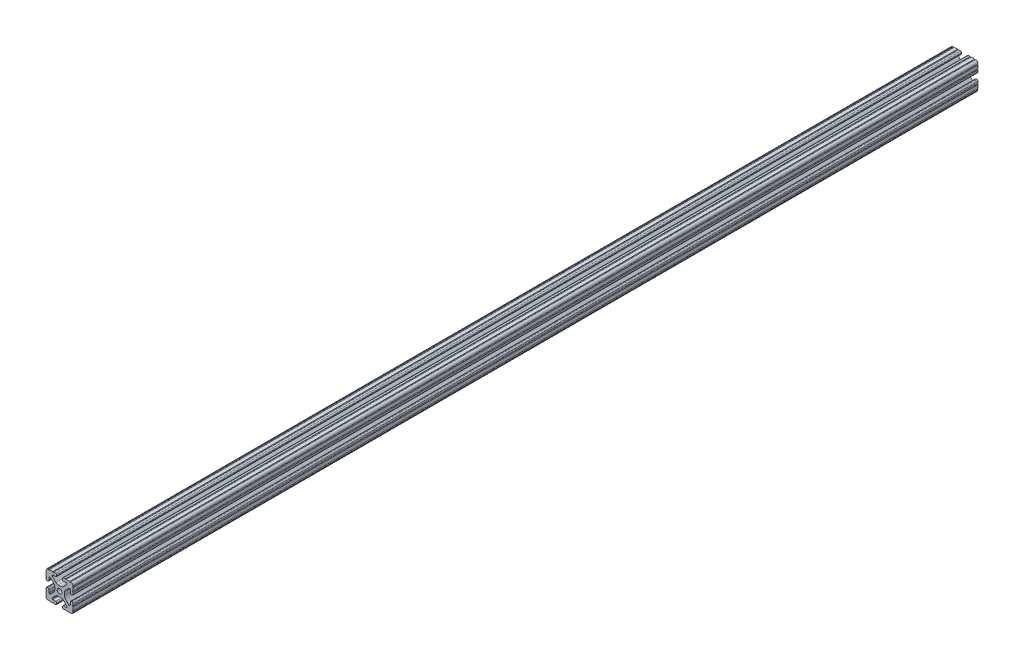
SolidWorks part; units mm, degrees
material "6061 Alloy"
ref_plane "Front Plane" through (0, 0, 0) normal (0, 0, 1) x (1, 0, 0)
ref_plane "Top Plane" through (0, 0, 0) normal (0, 1, 0) x (1, 0, 0)
ref_plane "Right Plane" through (0, 0, 0) normal (1, 0, 0) x (0, 0, -1)
sketch "Sketch1" plane through (0, 0, 0) normal (0, 0, 1) x (1, 0, 0)
  line L0 (0, 25.6181) -> (0, -24.623) construction
  line L1 (-20.8943, 0) -> (20.4607, 0) construction
  line L2 (-10.0229, 12.9148) -> (-5.2522, 8.144)
  line L3 (-10.287, 14.0843) -> (-10.287, 13.5524)
  line L4 (-5.6176, 14.986) -> (-9.3853, 14.986)
  line L5 (-4.064, 17.4964) -> (-4.064, 16.5396)
  line L6 (-7.9742, 19.05) -> (-5.6176, 19.05)
  line L7 (-14.3277, 19.05) -> (-9.4982, 19.05)
  line L8 (-19.05, 9.4961) -> (-19.05, 14.3277)
  line L9 (-19.05, 5.6176) -> (-19.05, 7.9763)
  line L10 (-16.5396, 4.064) -> (-17.4964, 4.064)
  line L11 (-14.986, 9.3853) -> (-14.986, 5.6176)
  line L12 (-13.516, 10.287) -> (-14.0843, 10.287)
  line L13 (-8.1476, 5.2921) -> (-12.8784, 10.0229)
  line L14 (-6.7564, -1.9335) -> (-6.7564, 1.9335)
  line L15 (-12.8784, -10.0229) -> (-8.1476, -5.2921)
  line L16 (-14.0843, -10.287) -> (-13.516, -10.287)
  line L17 (-14.986, -5.6176) -> (-14.986, -9.3853)
  line L18 (-17.4964, -4.064) -> (-16.5396, -4.064)
  line L19 (-19.05, -7.9763) -> (-19.05, -5.6176)
  line L20 (-19.05, -14.3277) -> (-19.05, -9.4961)
  line L21 (-9.4961, -19.05) -> (-14.3277, -19.05)
  line L22 (-5.6176, -19.05) -> (-7.9763, -19.05)
  line L23 (-4.064, -17.4964) -> (-4.064, -16.5396)
  line L24 (10.0229, -12.9148) -> (5.2522, -8.144)
  line L25 (10.287, -14.0843) -> (10.287, -13.5524)
  line L26 (5.6176, -14.986) -> (9.3853, -14.986)
  line L28 (-1.9022, 6.7564) -> (1.9022, 6.7564)
  line L29 (-1.9022, -6.7564) -> (1.9022, -6.7564)
  line L31 (-5.6176, -14.986) -> (-9.3853, -14.986)
  line L32 (-10.287, -14.0843) -> (-10.287, -13.5524)
  line L33 (-10.0229, -12.9148) -> (-5.2522, -8.144)
  line L66 (4.064, -16.5396) -> (4.064, -17.4964)
  line L67 (5.6176, -19.05) -> (7.9763, -19.05)
  line L68 (9.4961, -19.05) -> (14.3277, -19.05)
  line L69 (19.05, -14.3277) -> (19.05, -9.4961)
  line L70 (19.05, -7.9763) -> (19.05, -5.6176)
  line L71 (17.4964, -4.064) -> (16.5396, -4.064)
  line L72 (14.986, -5.6176) -> (14.986, -9.3853)
  line L73 (14.0843, -10.287) -> (13.516, -10.287)
  line L74 (12.8784, -10.0229) -> (8.1476, -5.2921)
  line L75 (6.7564, -1.9335) -> (6.7564, 1.9335)
  line L76 (8.1476, 5.2921) -> (12.8784, 10.0229)
  line L77 (13.516, 10.287) -> (14.0843, 10.287)
  line L78 (14.986, 9.3853) -> (14.986, 5.6176)
  line L79 (16.5396, 4.064) -> (17.4964, 4.064)
  line L80 (19.05, 5.6176) -> (19.05, 7.9763)
  line L81 (19.05, 9.4961) -> (19.05, 14.3277)
  line L82 (14.3277, 19.05) -> (9.4982, 19.05)
  line L83 (7.9742, 19.05) -> (5.6176, 19.05)
  line L84 (4.064, 17.4964) -> (4.064, 16.5396)
  line L85 (5.6176, 14.986) -> (9.3853, 14.986)
  line L86 (10.287, 14.0843) -> (10.287, 13.5524)
  line L87 (10.0229, 12.9148) -> (5.2522, 8.144)
  arc A0 (-10.0229, 12.9148) -> (-10.287, 13.5524) centre (-9.3853, 13.5524) cw
  circle A1 centre (0, 0) radius 3.3274
  arc A2 (-10.287, 14.0843) -> (-9.3853, 14.986) centre (-9.3853, 14.0843) cw
  arc A3 (-4.064, 16.5396) -> (-5.6176, 14.986) centre (-5.6176, 16.5396) cw
  arc A4 (-5.6176, 19.05) -> (-4.064, 17.4964) centre (-5.6176, 17.4964) cw
  arc A5 (-7.9742, 19.05) -> (-9.4982, 19.05) centre (-8.7362, 19.05) cw
  arc A6 (-14.3277, 19.05) -> (-15.8475, 19.05) centre (-15.0876, 18.9933) cw
  arc A7 (-19.05, 15.8475) -> (-15.8475, 19.05) centre (-15.8751, 15.8751) cw
  arc A8 (-19.05, 15.8475) -> (-19.05, 14.3277) centre (-18.9933, 15.0876) cw
  arc A9 (-19.05, 9.4961) -> (-19.05, 7.9763) centre (-18.9933, 8.7362) cw
  arc A10 (-17.4964, 4.064) -> (-19.05, 5.6176) centre (-17.4964, 5.6176) cw
  arc A11 (-14.986, 5.6176) -> (-16.5396, 4.064) centre (-16.5396, 5.6176) cw
  arc A12 (-14.986, 9.3853) -> (-14.0843, 10.287) centre (-14.0843, 9.3853) cw
  arc A13 (-13.516, 10.287) -> (-12.8784, 10.0229) centre (-13.516, 9.3853) cw
  arc A14 (-8.1476, 5.2921) -> (-6.7564, 1.9335) centre (-11.5062, 1.9335) cw
  arc A15 (-6.7564, -1.9335) -> (-8.1476, -5.2921) centre (-11.5062, -1.9335) cw
  arc A16 (-12.8784, -10.0229) -> (-13.516, -10.287) centre (-13.516, -9.3853) cw
  arc A17 (-14.0843, -10.287) -> (-14.986, -9.3853) centre (-14.0843, -9.3853) cw
  arc A18 (-16.5396, -4.064) -> (-14.986, -5.6176) centre (-16.5396, -5.6176) cw
  arc A19 (-19.05, -5.6176) -> (-17.4964, -4.064) centre (-17.4964, -5.6176) cw
  arc A20 (-19.05, -7.9763) -> (-19.05, -9.4961) centre (-18.9933, -8.7362) cw
  arc A21 (-19.05, -14.3277) -> (-19.05, -15.8475) centre (-18.9933, -15.0876) cw
  arc A22 (-15.8475, -19.05) -> (-19.05, -15.8475) centre (-15.8751, -15.8751) cw
  arc A23 (-15.8475, -19.05) -> (-14.3277, -19.05) centre (-15.0876, -18.9933) cw
  arc A24 (-9.4961, -19.05) -> (-7.9763, -19.05) centre (-8.7362, -18.9933) cw
  arc A25 (-4.064, -17.4964) -> (-5.6176, -19.05) centre (-5.6176, -17.4964) cw
  arc A26 (-5.2522, -8.144) -> (-1.9022, -6.7564) centre (-1.9022, -11.494) cw
  arc A27 (1.9022, -6.7564) -> (5.2522, -8.144) centre (1.9022, -11.494) cw
  arc A28 (10.0229, -12.9148) -> (10.287, -13.5524) centre (9.3853, -13.5524) cw
  arc A29 (10.287, -14.0843) -> (9.3853, -14.986) centre (9.3853, -14.0843) cw
  arc A30 (4.064, -16.5396) -> (5.6176, -14.986) centre (5.6176, -16.5396) cw
  arc A31 (-4.064, -16.5396) -> (-5.6176, -14.986) centre (-5.6176, -16.5396) ccw
  arc A32 (-10.287, -14.0843) -> (-9.3853, -14.986) centre (-9.3853, -14.0843) ccw
  arc A33 (-10.0229, -12.9148) -> (-10.287, -13.5524) centre (-9.3853, -13.5524) ccw
  arc A79 (4.064, -17.4964) -> (5.6176, -19.05) centre (5.6176, -17.4964) ccw
  arc A80 (9.4961, -19.05) -> (7.9763, -19.05) centre (8.7362, -18.9933) ccw
  arc A81 (15.8475, -19.05) -> (14.3277, -19.05) centre (15.0876, -18.9933) ccw
  arc A82 (15.8475, -19.05) -> (19.05, -15.8475) centre (15.8751, -15.8751) ccw
  arc A83 (19.05, -14.3277) -> (19.05, -15.8475) centre (18.9933, -15.0876) ccw
  arc A84 (19.05, -7.9763) -> (19.05, -9.4961) centre (18.9933, -8.7362) ccw
  arc A85 (19.05, -5.6176) -> (17.4964, -4.064) centre (17.4964, -5.6176) ccw
  arc A86 (16.5396, -4.064) -> (14.986, -5.6176) centre (16.5396, -5.6176) ccw
  arc A87 (14.0843, -10.287) -> (14.986, -9.3853) centre (14.0843, -9.3853) ccw
  arc A88 (12.8784, -10.0229) -> (13.516, -10.287) centre (13.516, -9.3853) ccw
  arc A89 (6.7564, -1.9335) -> (8.1476, -5.2921) centre (11.5062, -1.9335) ccw
  arc A90 (8.1476, 5.2921) -> (6.7564, 1.9335) centre (11.5062, 1.9335) ccw
  arc A91 (13.516, 10.287) -> (12.8784, 10.0229) centre (13.516, 9.3853) ccw
  arc A92 (14.986, 9.3853) -> (14.0843, 10.287) centre (14.0843, 9.3853) ccw
  arc A93 (14.986, 5.6176) -> (16.5396, 4.064) centre (16.5396, 5.6176) ccw
  arc A94 (17.4964, 4.064) -> (19.05, 5.6176) centre (17.4964, 5.6176) ccw
  arc A95 (19.05, 9.4961) -> (19.05, 7.9763) centre (18.9933, 8.7362) ccw
  arc A96 (19.05, 15.8475) -> (19.05, 14.3277) centre (18.9933, 15.0876) ccw
  arc A97 (19.05, 15.8475) -> (15.8475, 19.05) centre (15.8751, 15.8751) ccw
  arc A98 (14.3277, 19.05) -> (15.8475, 19.05) centre (15.0876, 18.9933) ccw
  arc A99 (7.9742, 19.05) -> (9.4982, 19.05) centre (8.7362, 19.05) ccw
  arc A100 (5.6176, 19.05) -> (4.064, 17.4964) centre (5.6176, 17.4964) ccw
  arc A101 (4.064, 16.5396) -> (5.6176, 14.986) centre (5.6176, 16.5396) ccw
  arc A102 (10.287, 14.0843) -> (9.3853, 14.986) centre (9.3853, 14.0843) ccw
  arc A103 (10.0229, 12.9148) -> (10.287, 13.5524) centre (9.3853, 13.5524) ccw
  arc A104 (1.9022, 6.7564) -> (5.2522, 8.144) centre (1.9022, 11.494) ccw
  arc A105 (-5.2522, 8.144) -> (-1.9022, 6.7564) centre (-1.9022, 11.494) ccw
  dimension "D1" = 6.6548
  dimension "D2" = 19.05
  dimension "D3" = 38.1
  dimension "D4" = 20.574
  dimension "D5" = 13.5128
  dimension "D6" = 4.064
  dimension "D7" = 8.128
  dimension "D8" = 4.064
  dimension "D9" = 12.2936
extrude "Extrude1" add sketch "Sketch1" against normal blind 1270
